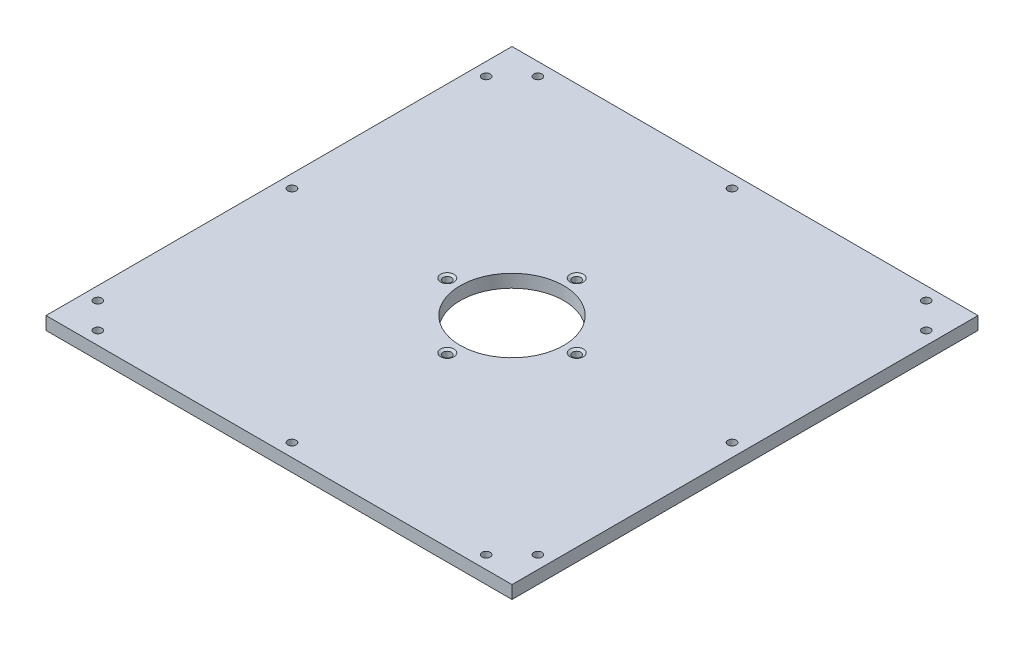
SolidWorks part; units mm, degrees
ref_plane "Front Plane" through (0, 0, 0) normal (0, 0, 1) x (1, 0, 0)
ref_plane "Top Plane" through (0, 0, 0) normal (0, 1, 0) x (1, 0, 0)
ref_plane "Right Plane" through (0, 0, 0) normal (1, 0, 0) x (0, 0, -1)
sketch "Sketch1" plane through (0, 0, 0) normal (0, 1, 0) x (1, 0, 0)
  line L0 (0, 90) -> (180, 90) construction
  line L1 (0, 0) -> (180, 0)
  line L2 (0, 0) -> (0, 180)
  line L3 (0, 180) -> (180, 180)
  line L4 (180, 0) -> (180, 180)
  line L5 (90, 180) -> (90, 0) construction
  line L6 (5, 180) -> (5, 0) construction
  line L7 (0, 175) -> (180, 175) construction
  circle A0 centre (90, 90) radius 20
  circle A1 centre (5, 165) radius 1.6
  circle A2 centre (5, 90) radius 1.6
  circle A3 centre (5, 15) radius 1.6
  circle A4 centre (175, 15) radius 1.6
  circle A5 centre (175, 90) radius 1.6
  circle A6 centre (175, 165) radius 1.6
  circle A7 centre (15, 175) radius 1.6
  circle A8 centre (90, 175) radius 1.6
  circle A9 centre (165, 175) radius 1.6
  circle A10 centre (165, 5) radius 1.6
  circle A11 centre (90, 5) radius 1.6
  circle A12 centre (15, 5) radius 1.6
  circle A13 centre (90, 90) radius 25 construction
  circle A14 centre (90, 115) radius 1.6
  circle A15 centre (90, 65) radius 1.6
  circle A16 centre (65, 90) radius 1.6
  circle A17 centre (115, 90) radius 1.6
  dimension "D3" = 40
  dimension "D5" = 3.2
  dimension "D6" = 3.2
  dimension "D7" = 15
  dimension "D8" = 5
  dimension "D9" = 3.2
  dimension "D10" = 3.2
  dimension "D13" = 3.2
  dimension "D14" = 3.2
  dimension "D1" = 180
  dimension "D2" = 180
  dimension "D4" = 5
  dimension "D11" = 15
  dimension "D12" = 5
extrude "Boss-Extrude1" add sketch "Sketch1" along normal blind 5
chamfer "Chamfer3" distance 1 angle 30 4 edges at (90, 5, -66.6) (115, 5, -91.6) (65, 5, -88.4) (90, 5, -113.4)
chamfer "Chamfer4" distance 1 angle 30 12 edges at (5, 0, -88.4) (5, 0, -16.6) (15, 0, -6.6) (90, 0, -6.6) (165, 0, -3.4) (175, 0, -13.4) (175, 0, -91.6) (5, 0, -163.4) (15, 0, -173.4) (90, 0, -173.4) (165, 0, -176.6) (175, 0, -166.6)
equation "\"m3 thread hole\"= 2.8mm"
equation "\"m3 passthrogh hole\"= 3.2mm"
